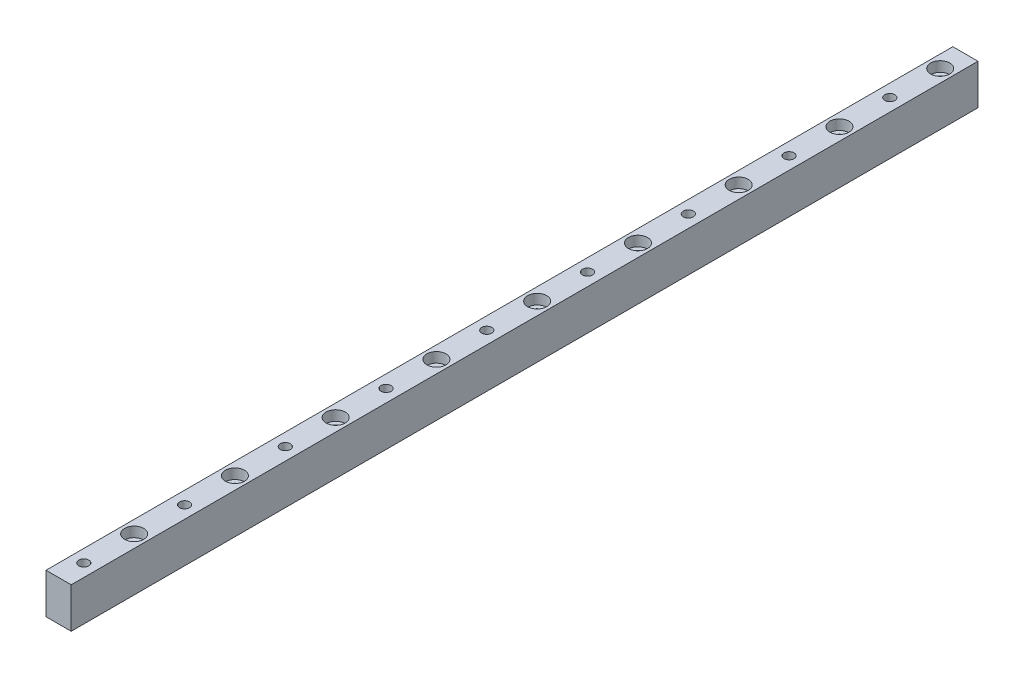
SolidWorks part; units mm, degrees
ref_plane "Front Plane" through (0, 0, 0) normal (0, 0, 1) x (1, 0, 0)
ref_plane "Top Plane" through (0, 0, 0) normal (0, 1, 0) x (1, 0, 0)
ref_plane "Right Plane" through (0, 0, 0) normal (1, 0, 0) x (0, 0, -1)
sketch "Sketch1" plane through (0, 0, 0) normal (0, 0, 1) x (1, 0, 0)
  line L1 (2.5, 4) -> (-2.5, 4)
  line L2 (2.5, 4) -> (2.5, -4)
  line L3 (2.5, -4) -> (-2.5, -4)
  line L4 (-2.5, 4) -> (-2.5, -4)
  line L5 (2.5, 4) -> (-2.5, -4) construction
  line L6 (2.5, -4) -> (-2.5, 4) construction
  point P0 (0, 0)
  dimension "D1" = 5
  dimension "D2" = 8
extrude "Boss-Extrude1" add sketch "Sketch1" along normal blind 185
sketch "Sketch2" plane through (0, 4, 0) normal (0, 1, 0) x (1, 0, 0)
  line L0 (2.5, 0) -> (-2.5, 0) construction
  circle A0 centre (0, -20) radius 1
  circle A1 centre (0, -40) radius 1
  circle A2 centre (0, -60) radius 1
  circle A3 centre (0, -80) radius 1
  circle A4 centre (0, -100) radius 1
  circle A5 centre (0, -120) radius 1
  circle A6 centre (0, -140) radius 1
  circle A7 centre (0, -160) radius 1
  circle A8 centre (0, -180) radius 1
  dimension "D1" = 20
  dimension "D2" = 9
extrude "Cut-Extrude2" cut sketch "Sketch2" against normal blind 2
hole_wizard "Ø2.0 (2) Diameter Hole1" positions "3DSketch1" profile "Sketch4" hole size "Ø2.0" standard "ISO"
sketch3d "3DSketch1"
  line L0 (0, 2, 20) -> (0, 4, 20) construction
  line L1 (0, 2, 40) -> (0, 4, 40) construction
  point P0 (0, 4, 20)
  point P5 (0, 4, 40)
sketch "Sketch4" plane through (0, 4, 20) normal (1, 0, 0) x (0, 0, 1)
  line L0 (0, 0) -> (0, 2.6009)
  line L1 (0, 2.6009) -> (1, 2)
  line L2 (1, 2) -> (1, 0)
  line L5 (1, 0) -> (0, 0)
  line L10 (0, 2.6009) -> (-1, 2) construction
  line L11 (0, -6.35) -> (0, 107.95) construction
  dimension "Hole Dia." = 2
  dimension "Hole Depth" = 2
  dimension "Drill Angle" = 118
pattern_linear "LPattern1" count 8 spacing 20 along (0, 0, 1) of "Ø2.0 (2) Diameter Hole1"
sketch "Sketch6" plane through (0, 4, 0) normal (0, 1, 0) x (1, 0, 0)
  line L0 (2.5, 0) -> (-2.5, 0) construction
  circle A0 centre (0, -30) radius 1
  circle A1 centre (0, -50) radius 1
  circle A2 centre (0, -70) radius 1
  circle A3 centre (0, -90) radius 1
  circle A4 centre (0, -110) radius 1
  circle A5 centre (0, -130) radius 1
  circle A6 centre (0, -150) radius 1
  circle A7 centre (0, -170) radius 1
  circle A8 centre (0, -190) radius 1
  circle A9 centre (0, -10) radius 1
  dimension "D1" = 9
  dimension "D2" = 10
extrude "Cut-Extrude3" cut sketch "Sketch6" against normal through all
sketch "Sketch8" plane through (0, 4, 0) normal (0, 1, 0) x (1, 0, 0)
  circle A0 centre (0, -10) radius 1.9
  circle A1 centre (0, -30) radius 1.9
  circle A2 centre (0, -50) radius 1.9
  circle A3 centre (0, -70) radius 1.9
  circle A4 centre (0, -90) radius 1.9
  circle A5 centre (0, -110) radius 1.9
  circle A6 centre (0, -130) radius 1.9
  circle A7 centre (0, -150) radius 1.9
  circle A8 centre (0, -170) radius 1.9
  circle A9 centre (0, -190) radius 1.9
  dimension "D1" = 10
  dimension "D2" = 3.8
extrude "Cut-Extrude4" cut sketch "Sketch8" against normal blind 2
sketch "Sketch9" plane through (0, 0, 0) normal (0, 0, -1) x (-1, 0, 0)
  line L8 (2.5, -4) -> (2.5, 4)
  line L9 (2.5, 4) -> (-2.5, 4)
  line L10 (-2.5, 4) -> (-2.5, -4)
  line L11 (-2.5, -4) -> (2.5, -4)
  line L12 (2.5, -4) -> (2.5, 4)
  line L13 (2.5, 4) -> (-2.5, 4)
  line L14 (-2.5, 4) -> (-2.5, -4)
  line L15 (-2.5, -4) -> (2.5, -4)
  dimension "D1" = 0
extrude "Cut-Extrude5" cut sketch "Sketch9" against normal blind 5
